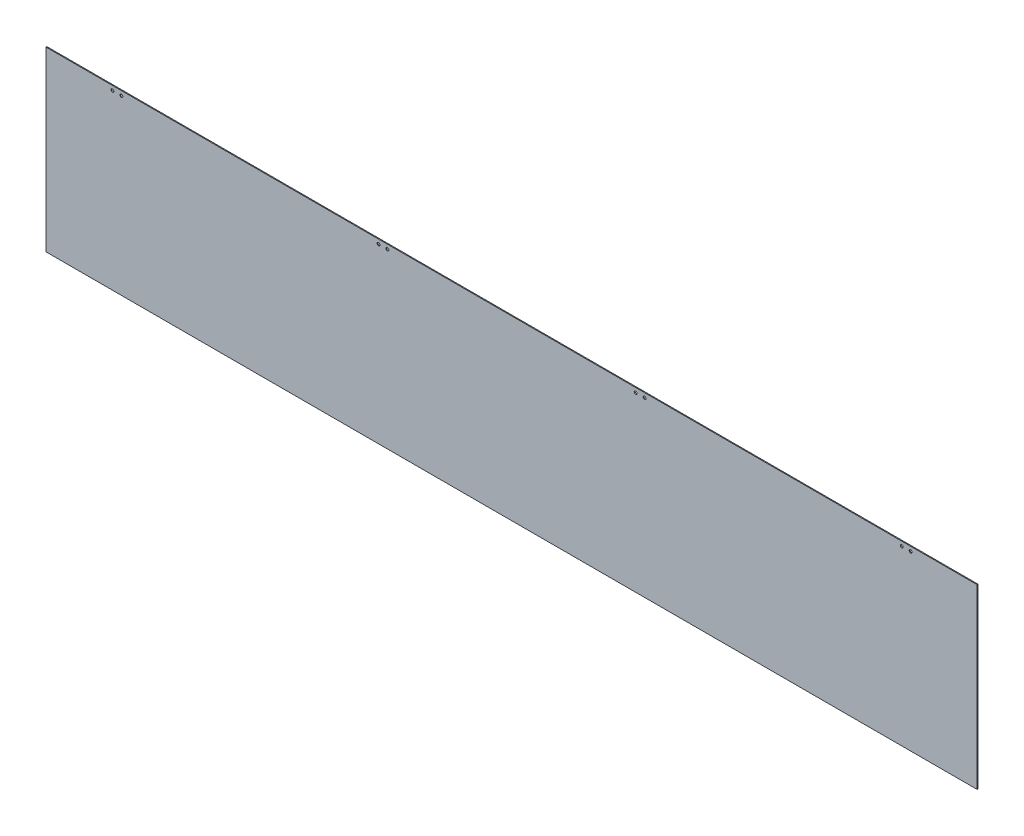
SolidWorks part; units mm, degrees
ref_plane "Front Plane" through (0, 0, 0) normal (0, 0, 1) x (1, 0, 0)
ref_plane "Top Plane" through (0, 0, 0) normal (0, 1, 0) x (1, 0, 0)
ref_plane "Right Plane" through (0, 0, 0) normal (1, 0, 0) x (0, 0, -1)
sketch "Sketch1" plane through (0, 0, 0) normal (0, 0, 1) x (1, 0, 0)
  line L1 (-525, -100) -> (525, -100)
  line L2 (-525, -100) -> (-525, 100)
  line L3 (-525, 100) -> (525, 100)
  line L4 (525, -100) -> (525, 100)
  line L5 (-525, -100) -> (525, 100) construction
  line L6 (-525, 100) -> (525, -100) construction
  point P0 (0, 0)
  dimension "D1" = 1050
  dimension "D2" = 200
extrude "Boss-Extrude1" add sketch "Sketch1" along normal blind 1 contours L2 L1 L4 L3
hole_wizard "M4x0.7 Tapped Hole1" positions "Sketch2" profile "Sketch3" tap size "M4x0.7" standard "ANSI Metric" end condition through all
sketch "Sketch2" plane through (0, 0, 1) normal (0, 0, 1) x (1, 0, 0)
  line L0 (-450, 95) -> (-440, 95)
  line L2 (-525, 100) -> (525, 100) construction
  line L3 (-150, 95) -> (-140, 95)
  point P0 (-450, 95)
  point P1 (-440, 95)
  point P7 (-445, 95)
  point P18 (-150, 95)
  point P19 (-140, 95)
  dimension "D1" = 10
  dimension "D2" = 5
  dimension "D3" = 80
  dimension "D4" = 2
sketch "Sketch3" plane through (-450, 95, 1) normal (1, 0, 0) x (0, -1, 0)
  line L0 (0, 0) -> (0, 1)
  line L1 (0, 1) -> (1.65, 1)
  line L2 (1.65, 1) -> (1.65, 0)
  line L5 (1.65, 0) -> (0, 0)
  line L11 (0, -6.35) -> (0, 107.95) construction
  dimension "Thru Tap Drill Dia." = 3.3
  dimension "Thru Tap Drill Depth" = 1
cosmetic thread "Hole Thread1"
cosmetic thread "Hole Thread2"
cosmetic thread "Hole Thread3"
cosmetic thread "Hole Thread4"
mirror "Mirror1" about plane through (0, 0, 0) normal (1, 0, 0) of "M4x0.7 Tapped Hole1"
cosmetic thread "Hole Thread5"
cosmetic thread "Hole Thread6"
cosmetic thread "Hole Thread7"
cosmetic thread "Hole Thread8"
